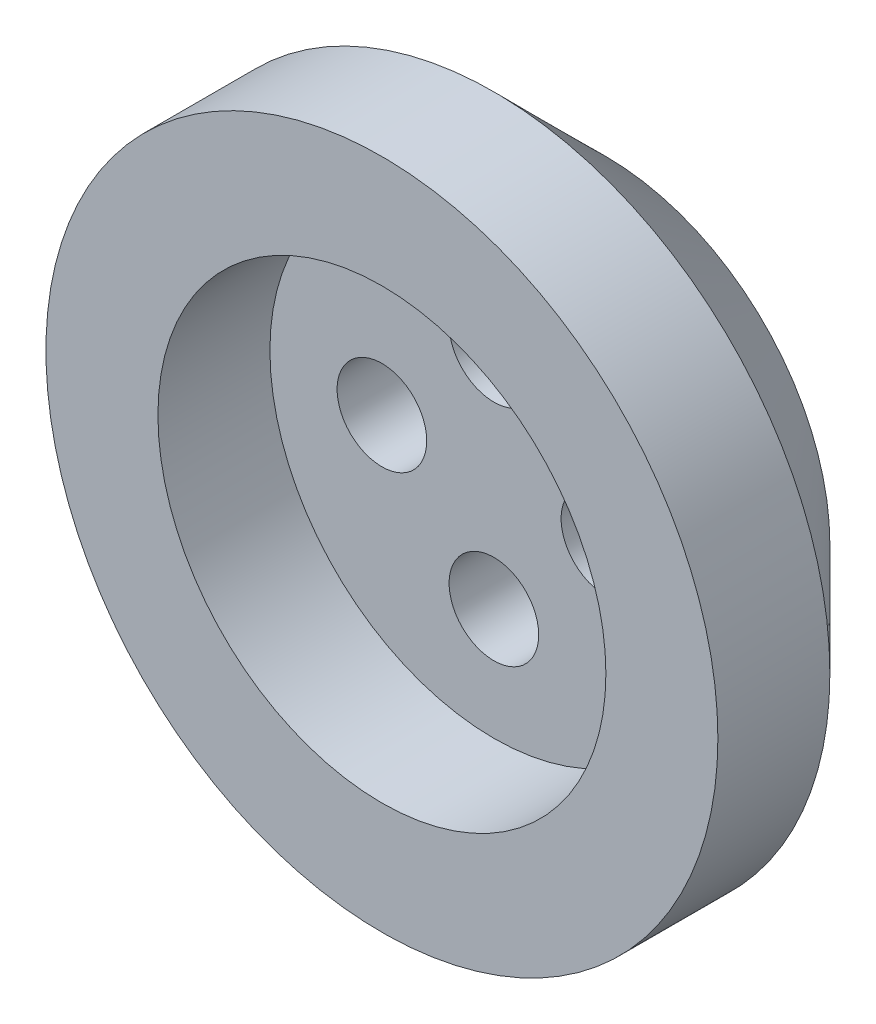
SolidWorks part; units mm, degrees
ref_plane "前视基准面" through (0, 0, 0) normal (0, 0, 1) x (1, 0, 0)
ref_plane "上视基准面" through (0, 0, 0) normal (0, 1, 0) x (1, 0, 0)
ref_plane "右视基准面" through (0, 0, 0) normal (1, 0, 0) x (0, 0, -1)
other "Configuration Table"
sketch "Sketch1" plane through (0, 0, 0) normal (0, 0, 1) x (1, 0, 0)
  circle A0 centre (0, 0) radius 7.5
  dimension "D1" = 15
extrude "Boss-Extrude1" add sketch "Sketch1" along normal blind 5
sketch "Sketch2" plane through (0, 0, 5) normal (0, 0, 1) x (1, 0, 0)
  circle A0 centre (0, 0) radius 5
  dimension "D1" = 10
extrude "Cut-Extrude1" cut sketch "Sketch2" against normal blind 2.5
chamfer "Chamfer1" distance 2.5 angle 45 1 edges at (7.5, 0, 0)
sketch "Sketch3" plane through (0, 0, 2.5) normal (0, 0, 1) x (1, 0, 0)
  circle A0 centre (0, 0) radius 2.5 construction
  circle A1 centre (0, 2.5) radius 1
  circle A2 centre (0, 0) radius 2.5 construction
  circle A3 centre (2.5, 0) radius 1
  circle A4 centre (0, 0) radius 2.5 construction
  circle A5 centre (0, -2.5) radius 1
  circle A6 centre (0, 0) radius 2.5 construction
  circle A7 centre (-2.5, 0) radius 1
  point P17 (0, 0)
  dimension "D1" = 5
  dimension "D2" = 2
extrude "Cut-Extrude2" cut sketch "Sketch3" against normal blind 2.5
